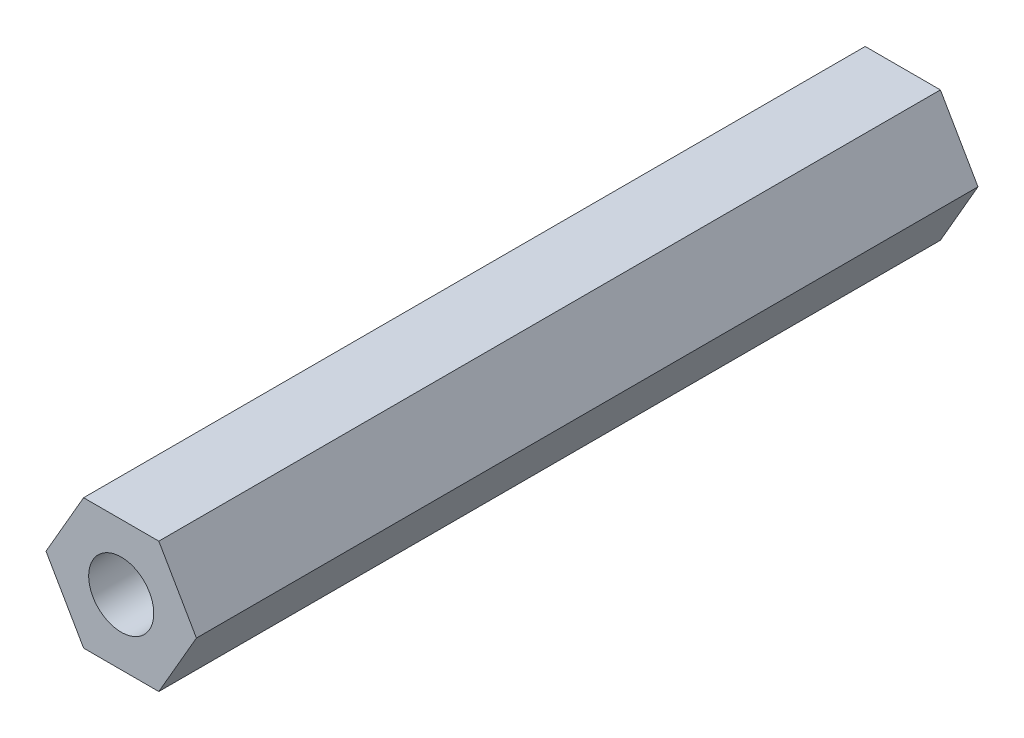
SolidWorks part; units mm, degrees
material "1060 Alloy"
ref_plane "Front Plane" through (0, 0, 0) normal (0, 0, 1) x (1, 0, 0)
ref_plane "Top Plane" through (0, 0, 0) normal (0, 1, 0) x (1, 0, 0)
ref_plane "Right Plane" through (0, 0, 0) normal (1, 0, 0) x (0, 0, -1)
sketch "Sketch1" plane through (0, 0, 0) normal (0, 0, 1) x (1, 0, 0)
  line L1 (3.6662, 6.35) -> (-3.6662, 6.35)
  line L2 (-3.6662, 6.35) -> (-7.3323, 0)
  line L3 (-7.3323, 0) -> (-3.6662, -6.35)
  line L4 (-3.6662, -6.35) -> (3.6662, -6.35)
  line L5 (3.6662, -6.35) -> (7.3323, 0)
  line L6 (7.3323, 0) -> (3.6662, 6.35)
  circle A0 centre (0, 0) radius 6.35 construction
  circle A1 centre (0, 0) radius 3.175
  dimension "D2" = 6.35
  dimension "D1" = 12.7
extrude "Boss-Extrude1" add sketch "Sketch1" along normal blind 76.2
